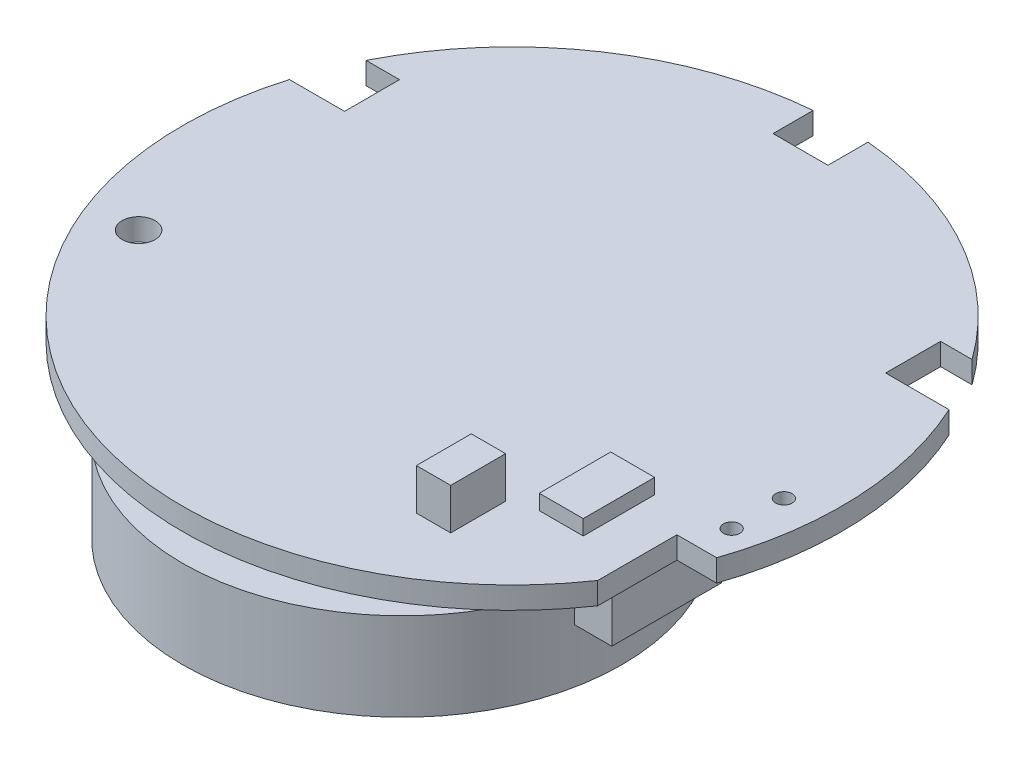
SolidWorks part; units mm, degrees
ref_plane "Front Plane" through (0, 0, 0) normal (0, 0, 1) x (1, 0, 0)
ref_plane "Top Plane" through (0, 0, 0) normal (0, 1, 0) x (1, 0, 0)
ref_plane "Right Plane" through (0, 0, 0) normal (1, 0, 0) x (0, 0, -1)
sketch "Sketch1" plane through (0, 0, 0) normal (0, 1, 0) x (1, 0, 0)
  circle A0 centre (0, 0) radius 12
extrude "Boss-Extrude1" add sketch "Sketch1" along normal blind 0.8 contours A0
sketch "Sketch2" plane through (0, 0.8, 0) normal (0, 1, 0) x (1, 0, 0)
  line L0 (-12, 12) -> (-12, 5.4) construction
  line L1 (-12, 12) -> (12, 12) construction
  line L2 (-12, 12) -> (-12, -12) construction
  line L3 (-12, -12) -> (12, -12) construction
  line L4 (12, 12) -> (12, -12) construction
  line L5 (-9.5, 3.4) -> (-12, 3.4)
  line L6 (12, 12) -> (1, 12) construction
  line L7 (1, 12) -> (1, 10.5)
  line L8 (1, 10.5) -> (-1, 10.5)
  line L9 (-1, 10.5) -> (-1, 12)
  line L10 (-1, 12) -> (1, 12)
  line L11 (-12, 5.4) -> (-9.5, 5.4)
  line L12 (-9.5, 5.4) -> (-9.5, 3.4)
  line L13 (-12, 3.4) -> (-12, 5.4)
  line L14 (12, 12) -> (12, 7)
  line L15 (12, 7) -> (8.6, 7)
  line L16 (8.6, 7) -> (8.6, 5)
  line L17 (8.6, 5) -> (12, 5)
  line L18 (12, 5) -> (12, 7)
  line L19 (12, -12) -> (12, -3.9)
  line L20 (12, -12) -> (9.9, -12)
  line L21 (9.9, -12) -> (9.9, -3.9)
  line L22 (9.9, -3.9) -> (12, -3.9)
  point P0 (0, 0)
  circle M19 centre (0, 0) radius 12
  dimension "D1" = 6.6
  dimension "D2" = 2
  dimension "D3" = 11
  dimension "D4" = 1.5
  dimension "D5" = 2
  dimension "D6" = 2.5
  dimension "D7" = 5
  dimension "D8" = 3.4
  dimension "D9" = 2
  dimension "D10" = 8.1
  dimension "D11" = 2.1
extrude "Cut-Extrude1" cut sketch "Sketch2" against normal blind 0.8 contours L12 L11 L5 M19 | L9 L8 L7 M19 | L16 L17 L15 M19 | L22 L21 M19
sketch "Sketch3" plane through (0, 0.8, 0) normal (0, 1, 0) x (1, 0, 0)
  line L0 (0, 0) -> (-9.5059, -4.0939) construction
  line L1 (0, 0) -> (10.6998, -0.8045) construction
  line L2 (0, 0) -> (10.7027, -2.7082) construction
  circle A0 centre (-9.5059, -4.0939) radius 0.6
  circle A1 centre (10.7027, -2.7082) radius 0.3
  circle A2 centre (10.6998, -0.8045) radius 0.3
  dimension "D1" = 10.73
  dimension "D2" = 10.35
  dimension "D3" = 11.04
extrude "Cut-Extrude2" cut sketch "Sketch3" against normal blind 0.8
sketch "Sketch4" plane through (0, 0, 0) normal (0, -1, 0) x (-1, 0, 0)
  line L1 (-4, -2) -> (4, -2)
  line L2 (-4, -2) -> (-4, -6)
  line L3 (-4, -6) -> (4, -6)
  line L4 (4, -2) -> (4, -6)
  line L5 (-4, -2) -> (4, -6) construction
  line L6 (-4, -6) -> (4, -2) construction
extrude "Boss-Extrude2" add sketch "Sketch4" along normal blind 1
sketch "Sketch5" plane through (0, -1, 0) normal (0, -1, 0) x (-1, 0, 0)
  circle A0 centre (0, -4) radius 8
extrude "Boss-Extrude3" add sketch "Sketch5" along normal blind 3.2
sketch "Sketch6" plane through (0, 0, 0) normal (0, -1, 0) x (1, 0, 0)
  line L0 (9.63, 12) -> (9.63, 6) construction
  line L5 (12, 12) -> (9.63, 12) construction
  line L6 (9.63, 6) -> (9.63, 2)
  line L7 (9.63, 2) -> (8.28, 2)
  line L8 (8.28, 2) -> (8.28, 6)
  line L9 (8.28, 6) -> (9.63, 6)
  point P0 (0, 0)
  point P2 (12, 12)
  dimension "D1" = 6
  dimension "D2" = 2.37
  dimension "D3" = 4
  dimension "D4" = 1.35
extrude "Boss-Extrude4" add sketch "Sketch6" along normal blind 1.8
sketch "Sketch7" plane through (0, 0.8, 0) normal (0, 1, 0) x (1, 0, 0)
  line L5 (4.475, -5.96) -> (5.725, -5.96)
  line L6 (4.475, -5.96) -> (4.475, -7.96)
  line L7 (4.475, -7.96) -> (5.725, -7.96)
  line L8 (5.725, -5.96) -> (5.725, -7.96)
  line L9 (4.475, -5.96) -> (5.725, -7.96) construction
  line L10 (4.475, -7.96) -> (5.725, -5.96) construction
  point P0 (5.1, -6.96)
  point P5 (0, 0)
  point P6 (0, 0)
extrude "Boss-Extrude5" add sketch "Sketch7" along normal blind 1.5
sketch "Sketch8" plane through (0, 0.8, 0) normal (0, 1, 0) x (1, 0, 0)
  line L0 (12, -12) -> (7.435, -12)
  line L6 (6.635, -3.045) -> (8.235, -3.045)
  line L9 (-12, -12) -> (12, -12) construction
  line L10 (12, 12) -> (12, -12) construction
  line L11 (7.435, -12) -> (7.435, -4.345)
  line L12 (6.635, -3.045) -> (6.635, -5.645)
  line L13 (6.635, -5.645) -> (8.235, -5.645)
  line L14 (8.235, -3.045) -> (8.235, -5.645)
  line L15 (6.635, -3.045) -> (8.235, -5.645) construction
  line L16 (6.635, -5.645) -> (8.235, -3.045) construction
  point P5 (0, 0)
  dimension "D1" = 4.565
  dimension "D2" = 7.655
extrude "Boss-Extrude6" add sketch "Sketch8" along normal blind 0.55
